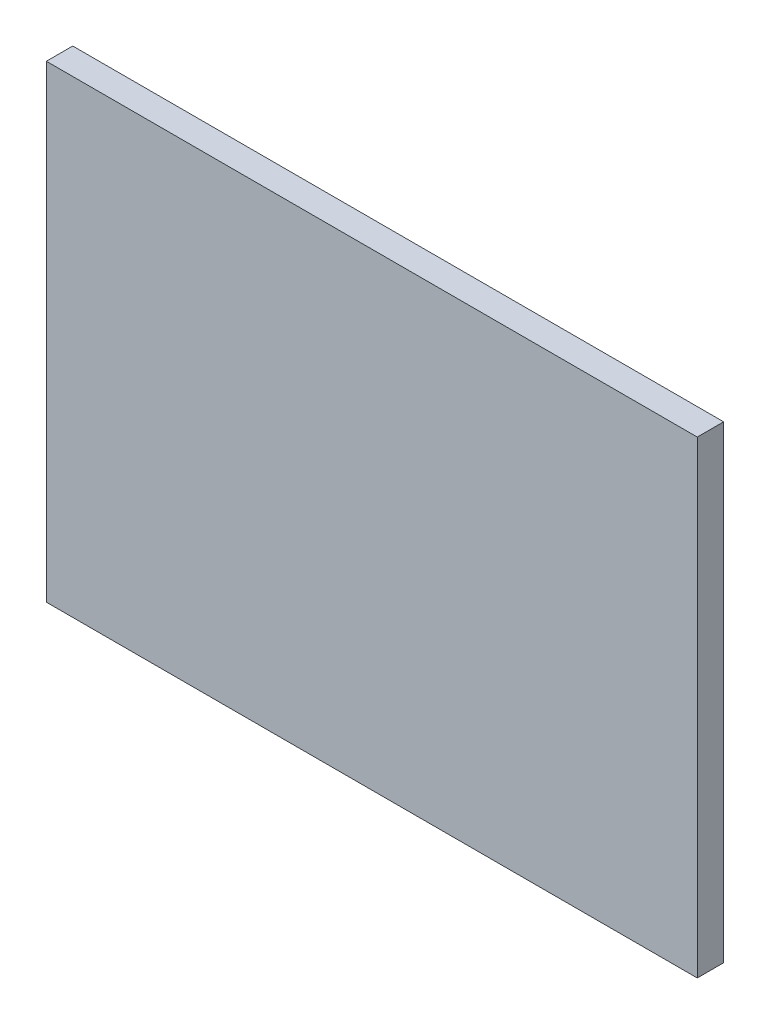
SolidWorks part; units mm, degrees
ref_plane "Plano frontal" through (0, 0, 0) normal (0, 0, 1) x (1, 0, 0)
ref_plane "Plano superior" through (0, 0, 0) normal (0, 1, 0) x (1, 0, 0)
ref_plane "Plano direito" through (0, 0, 0) normal (1, 0, 0) x (0, 0, -1)
sketch "Esboço1" plane through (0, 0, 0) normal (0, 0, 1) x (1, 0, 0)
  line L1 (-185, 133.15) -> (185, 133.15)
  line L2 (-185, 133.15) -> (-185, -133.15)
  line L3 (-185, -133.15) -> (185, -133.15)
  line L4 (185, 133.15) -> (185, -133.15)
  line L5 (-185, 133.15) -> (185, -133.15) construction
  line L6 (-185, -133.15) -> (185, 133.15) construction
  point P0 (0, 0)
  dimension "D1" = 370
  dimension "D2" = 266.3
extrude "Ressalto-extrusão1" add sketch "Esboço1" along normal blind 15
